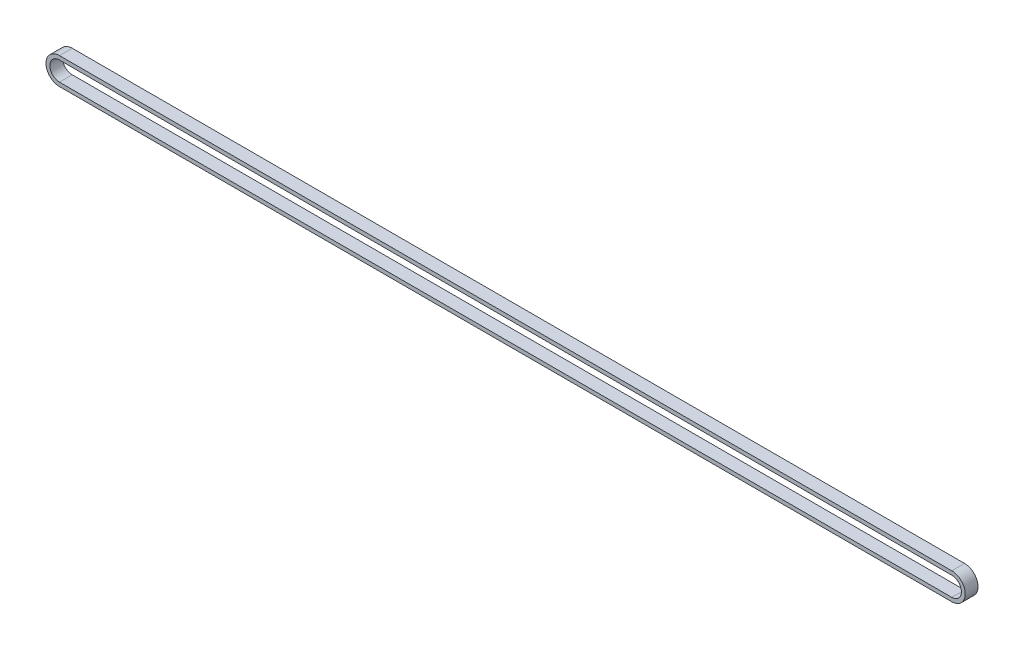
SolidWorks part; units mm, degrees
ref_plane "Front Plane" through (0, 0, 0) normal (0, 0, 1) x (1, 0, 0)
ref_plane "Top Plane" through (0, 0, 0) normal (0, 1, 0) x (1, 0, 0)
ref_plane "Right Plane" through (0, 0, 0) normal (1, 0, 0) x (0, 0, -1)
sketch "Sketch1" plane through (0, 0, 0) normal (0, 0, 1) x (1, 0, 0)
  line L0 (-209.565, 0) -> (209.565, 0) construction
  line L1 (-209.565, 4.5) -> (209.565, 4.5)
  line L2 (-209.565, -4.5) -> (209.565, -4.5)
  arc A0 (-209.565, 4.5) -> (-209.565, -4.5) centre (-209.565, 0) ccw
  arc A1 (209.565, -4.5) -> (209.565, 4.5) centre (209.565, 0) ccw
  point P2 (0, 0)
  dimension "D2" = 4.5
  dimension "D1" = 419.13
extrude "Extrude-Thin1" add sketch "Sketch1" along normal blind 6 thin thin type one direction wall 1.8
